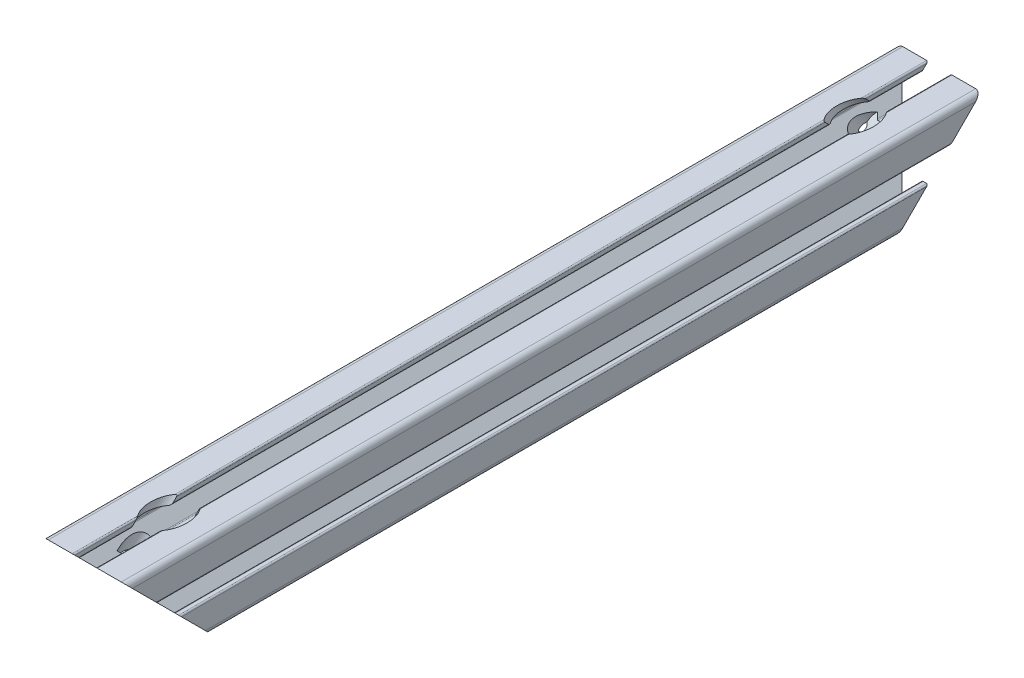
SolidWorks part; units mm, degrees
ref_plane "Front Plane" through (0, 0, 0) normal (0, 0, 1) x (1, 0, 0)
ref_plane "Top Plane" through (0, 0, 0) normal (0, 1, 0) x (1, 0, 0)
ref_plane "Right Plane" through (0, 0, 0) normal (1, 0, 0) x (0, 0, -1)
sketch "Sketch1" plane through (0, 0, 0) normal (0, 0, 1) x (1, 0, 0)
  line L0 (3.9799, -2.4733) -> (3.1981, -1.4942) construction
  line L1 (1.4942, -3.1981) -> (2.4733, -3.9799) construction
  line L2 (-2.4733, -3.9799) -> (-1.4942, -3.1981) construction
  line L3 (-3.1981, -1.4942) -> (-3.9799, -2.4733) construction
  line L4 (-3.9799, 2.4733) -> (-3.1981, 1.4942) construction
  line L5 (-1.4942, 3.1981) -> (-2.4733, 3.9799) construction
  line L6 (2.4733, 3.9799) -> (1.4942, 3.1981) construction
  line L7 (3.1981, 1.4942) -> (3.9799, 2.4733) construction
  line L8 (-12.6999, -13.6999) -> (-9.881, -13.6999)
  line L9 (-13.6999, -9.881) -> (-13.6999, -12.6999)
  line L10 (-9.88, -9.5) -> (-13.3189, -9.5)
  line L11 (-9.5, -13.3189) -> (-9.5, -9.88)
  line L12 (13.6999, -12.6999) -> (13.6999, -9.881)
  line L13 (9.881, -13.6999) -> (12.6999, -13.6999)
  line L14 (9.5, -9.88) -> (9.5, -13.3189)
  line L15 (13.3189, -9.5) -> (9.88, -9.5)
  line L16 (9.88, 9.5) -> (13.3189, 9.5)
  line L17 (9.5, 13.3189) -> (9.5, 9.88)
  line L18 (12.6999, 13.6999) -> (9.881, 13.6999)
  line L19 (13.6999, 9.881) -> (13.6999, 12.6999)
  line L20 (-13.6999, 12.6999) -> (-13.6999, 9.881)
  line L21 (-9.881, 13.6999) -> (-12.6999, 13.6999)
  line L22 (-9.5, 9.88) -> (-9.5, 13.3189)
  line L23 (-13.3189, 9.5) -> (-9.88, 9.5)
  line L24 (14.4999, -4) -> (13.2425, -4)
  line L25 (12.7425, -4.5) -> (12.7425, -7.7325)
  line L26 (12.2428, -8.25) -> (10.2602, -8.25)
  line L27 (9.9066, -8.1035) -> (5.9811, -4.178)
  line L28 (5.8347, -3.8245) -> (5.8347, -1.0125)
  line L29 (5.8347, -1.0125) -> (5.3247, -0.0625) construction
  line L30 (5.3247, -0.0625) -> (5.8347, 0.8875) construction
  line L31 (5.8347, 0.8875) -> (5.8347, 3.8245)
  line L32 (5.9811, 4.178) -> (9.9066, 8.1035)
  line L33 (10.2602, 8.25) -> (12.2428, 8.25)
  line L34 (12.7425, 7.7325) -> (12.7425, 4.5)
  line L35 (13.2425, 4) -> (14.4999, 4)
  line L36 (14.9999, 4.5) -> (14.9999, 12.9999)
  line L37 (12.9999, 14.9999) -> (4.5, 14.9999)
  line L38 (4, 14.4999) -> (4, 13.2425)
  line L39 (4.5, 12.7425) -> (7.7325, 12.7425)
  line L40 (8.25, 12.2428) -> (8.25, 10.2602)
  line L41 (8.1035, 9.9066) -> (4.178, 5.9811)
  line L42 (3.8245, 5.8347) -> (0.95, 5.8347)
  line L43 (0.95, 5.8347) -> (0, 5.3247) construction
  line L44 (0, 5.3247) -> (-0.95, 5.8347) construction
  line L45 (-0.95, 5.8347) -> (-3.8245, 5.8347)
  line L46 (-4.178, 5.9811) -> (-8.1035, 9.9066)
  line L47 (-8.25, 10.2602) -> (-8.25, 12.2428)
  line L48 (-7.7325, 12.7425) -> (-4.5, 12.7425)
  line L49 (-4, 13.2425) -> (-4, 14.4999)
  line L50 (-4.5, 14.9999) -> (-12.9999, 14.9999)
  line L51 (-14.9999, 12.9999) -> (-14.9999, 4.5)
  line L52 (-14.4999, 4) -> (-13.2425, 4)
  line L53 (-12.7425, 4.5) -> (-12.7425, 7.7325)
  line L54 (-12.2428, 8.25) -> (-10.2602, 8.25)
  line L55 (-9.9066, 8.1035) -> (-5.9811, 4.178)
  line L56 (-5.8347, 3.8245) -> (-5.8347, 0.8875)
  line L57 (-5.8347, 0.8875) -> (-5.3247, -0.0625) construction
  line L58 (-5.3247, -0.0625) -> (-5.8347, -1.0125) construction
  line L59 (-5.8347, -1.0125) -> (-5.8347, -3.8245)
  line L60 (-5.9811, -4.178) -> (-9.9066, -8.1035)
  line L61 (-10.2602, -8.25) -> (-12.2428, -8.25)
  line L62 (-12.7425, -7.7325) -> (-12.7425, -4.5)
  line L63 (-13.2425, -4) -> (-14.4999, -4)
  line L64 (-14.9999, -4.5) -> (-14.9999, -12.9999)
  line L65 (-12.9999, -14.9999) -> (-4.5, -14.9999)
  line L66 (-4, -14.4999) -> (-4, -13.2425)
  line L67 (-4.5, -12.7425) -> (-7.7325, -12.7425)
  line L68 (-8.25, -12.2428) -> (-8.25, -10.2602)
  line L69 (-8.1035, -9.9066) -> (-4.178, -5.9811)
  line L70 (-3.8245, -5.8347) -> (-0.95, -5.8347)
  line L71 (-0.95, -5.8347) -> (0, -5.3247) construction
  line L72 (0, -5.3247) -> (0.95, -5.8347) construction
  line L73 (0.95, -5.8347) -> (3.8245, -5.8347)
  line L74 (4.178, -5.9811) -> (8.1035, -9.9066)
  line L75 (8.25, -10.2602) -> (8.25, -12.2428)
  line L76 (7.7325, -12.7425) -> (4.5, -12.7425)
  line L77 (4, -13.2425) -> (4, -14.4999)
  line L78 (4.5, -14.9999) -> (12.9999, -14.9999)
  line L79 (14.9999, -12.9999) -> (14.9999, -4.5)
  line L80 (-5.8347, -1.0125) -> (-5.8347, 0.8875)
  line L81 (-0.95, 5.8347) -> (0.95, 5.8347)
  line L82 (5.8347, 0.8875) -> (5.8347, -1.0125)
  line L83 (-0.95, -5.8347) -> (0.95, -5.8347)
  arc A0 (2.4733, -3.9799) -> (3.9799, -2.4733) centre (3.1422, -3.1422) ccw construction
  arc A1 (-1.4942, -3.1981) -> (1.4942, -3.1981) centre (0, 0) ccw construction
  arc A2 (-3.9799, -2.4733) -> (-2.4733, -3.9799) centre (-3.1422, -3.1422) ccw construction
  arc A3 (-3.1981, 1.4942) -> (-3.1981, -1.4942) centre (0, 0) ccw construction
  arc A4 (-2.4733, 3.9799) -> (-3.9799, 2.4733) centre (-3.1422, 3.1422) ccw construction
  arc A5 (1.4942, 3.1981) -> (-1.4942, 3.1981) centre (0, 0) ccw construction
  arc A6 (3.9799, 2.4733) -> (2.4733, 3.9799) centre (3.1422, 3.1422) ccw construction
  arc A7 (3.1981, -1.4942) -> (3.1981, 1.4942) centre (0, 0) ccw construction
  arc A8 (-13.6999, -12.6999) -> (-12.6999, -13.6999) centre (-12.6999, -12.6999) ccw
  arc A9 (-13.3189, -9.5) -> (-13.6999, -9.881) centre (-13.3189, -9.881) ccw
  arc A10 (-9.5, -9.88) -> (-9.88, -9.5) centre (-9.88, -9.88) ccw
  arc A11 (-9.881, -13.6999) -> (-9.5, -13.3189) centre (-9.881, -13.3189) ccw
  arc A12 (12.6999, -13.6999) -> (13.6999, -12.6999) centre (12.6999, -12.6999) ccw
  arc A13 (9.5, -13.3189) -> (9.881, -13.6999) centre (9.881, -13.3189) ccw
  arc A14 (9.88, -9.5) -> (9.5, -9.88) centre (9.88, -9.88) ccw
  arc A15 (13.6999, -9.881) -> (13.3189, -9.5) centre (13.3189, -9.881) ccw
  arc A16 (9.5, 9.88) -> (9.88, 9.5) centre (9.88, 9.88) ccw
  arc A17 (9.881, 13.6999) -> (9.5, 13.3189) centre (9.881, 13.3189) ccw
  arc A18 (13.6999, 12.6999) -> (12.6999, 13.6999) centre (12.6999, 12.6999) ccw
  arc A19 (13.3189, 9.5) -> (13.6999, 9.881) centre (13.3189, 9.881) ccw
  arc A20 (14.9999, -4.5) -> (14.4999, -4) centre (14.4999, -4.5) ccw
  arc A21 (13.2425, -4) -> (12.7425, -4.5) centre (13.2425, -4.5) ccw
  arc A22 (12.2428, -8.25) -> (12.7425, -7.7325) centre (12.2428, -7.75) ccw
  arc A23 (9.9066, -8.1035) -> (10.2602, -8.25) centre (10.2602, -7.75) ccw
  arc A24 (5.8347, -3.8245) -> (5.9811, -4.178) centre (6.3347, -3.8245) ccw
  arc A25 (5.9811, 4.178) -> (5.8347, 3.8245) centre (6.3347, 3.8245) ccw
  arc A26 (10.2602, 8.25) -> (9.9066, 8.1035) centre (10.2602, 7.75) ccw
  arc A27 (12.7425, 7.7325) -> (12.2428, 8.25) centre (12.2428, 7.75) ccw
  arc A28 (12.7425, 4.5) -> (13.2425, 4) centre (13.2425, 4.5) ccw
  arc A29 (14.4999, 4) -> (14.9999, 4.5) centre (14.4999, 4.5) ccw
  arc A30 (14.9999, 12.9999) -> (12.9999, 14.9999) centre (12.9999, 12.9999) ccw
  arc A31 (4.5, 14.9999) -> (4, 14.4999) centre (4.5, 14.4999) ccw
  arc A32 (4, 13.2425) -> (4.5, 12.7425) centre (4.5, 13.2425) ccw
  arc A33 (8.25, 12.2428) -> (7.7325, 12.7425) centre (7.75, 12.2428) ccw
  arc A34 (8.1035, 9.9066) -> (8.25, 10.2602) centre (7.75, 10.2602) ccw
  arc A35 (3.8245, 5.8347) -> (4.178, 5.9811) centre (3.8245, 6.3347) ccw
  arc A36 (-4.178, 5.9811) -> (-3.8245, 5.8347) centre (-3.8245, 6.3347) ccw
  arc A37 (-8.25, 10.2602) -> (-8.1035, 9.9066) centre (-7.75, 10.2602) ccw
  arc A38 (-7.7325, 12.7425) -> (-8.25, 12.2428) centre (-7.75, 12.2428) ccw
  arc A39 (-4.5, 12.7425) -> (-4, 13.2425) centre (-4.5, 13.2425) ccw
  arc A40 (-4, 14.4999) -> (-4.5, 14.9999) centre (-4.5, 14.4999) ccw
  arc A41 (-12.9999, 14.9999) -> (-14.9999, 12.9999) centre (-12.9999, 12.9999) ccw
  arc A42 (-14.9999, 4.5) -> (-14.4999, 4) centre (-14.4999, 4.5) ccw
  arc A43 (-13.2425, 4) -> (-12.7425, 4.5) centre (-13.2425, 4.5) ccw
  arc A44 (-12.2428, 8.25) -> (-12.7425, 7.7325) centre (-12.2428, 7.75) ccw
  arc A45 (-9.9066, 8.1035) -> (-10.2602, 8.25) centre (-10.2602, 7.75) ccw
  arc A46 (-5.8347, 3.8245) -> (-5.9811, 4.178) centre (-6.3347, 3.8245) ccw
  arc A47 (-5.9811, -4.178) -> (-5.8347, -3.8245) centre (-6.3347, -3.8245) ccw
  arc A48 (-10.2602, -8.25) -> (-9.9066, -8.1035) centre (-10.2602, -7.75) ccw
  arc A49 (-12.7425, -7.7325) -> (-12.2428, -8.25) centre (-12.2428, -7.75) ccw
  arc A50 (-12.7425, -4.5) -> (-13.2425, -4) centre (-13.2425, -4.5) ccw
  arc A51 (-14.4999, -4) -> (-14.9999, -4.5) centre (-14.4999, -4.5) ccw
  arc A52 (-14.9999, -12.9999) -> (-12.9999, -14.9999) centre (-12.9999, -12.9999) ccw
  arc A53 (-4.5, -14.9999) -> (-4, -14.4999) centre (-4.5, -14.4999) ccw
  arc A54 (-4, -13.2425) -> (-4.5, -12.7425) centre (-4.5, -13.2425) ccw
  arc A55 (-8.25, -12.2428) -> (-7.7325, -12.7425) centre (-7.75, -12.2428) ccw
  arc A56 (-8.1035, -9.9066) -> (-8.25, -10.2602) centre (-7.75, -10.2602) ccw
  arc A57 (-3.8245, -5.8347) -> (-4.178, -5.9811) centre (-3.8245, -6.3347) ccw
  arc A58 (4.178, -5.9811) -> (3.8245, -5.8347) centre (3.8245, -6.3347) ccw
  arc A59 (8.25, -10.2602) -> (8.1035, -9.9066) centre (7.75, -10.2602) ccw
  arc A60 (7.7325, -12.7425) -> (8.25, -12.2428) centre (7.75, -12.2428) ccw
  arc A61 (4.5, -12.7425) -> (4, -13.2425) centre (4.5, -13.2425) ccw
  arc A62 (4, -14.4999) -> (4.5, -14.9999) centre (4.5, -14.4999) ccw
  arc A63 (12.9999, -14.9999) -> (14.9999, -12.9999) centre (12.9999, -12.9999) ccw
  arc A64 (-12.6999, 13.6999) -> (-13.6999, 12.6999) centre (-12.6999, 12.6999) ccw
  arc A65 (-9.5, 13.3189) -> (-9.881, 13.6999) centre (-9.881, 13.3189) ccw
  arc A66 (-9.88, 9.5) -> (-9.5, 9.88) centre (-9.88, 9.88) ccw
  arc A67 (-13.6999, 9.881) -> (-13.3189, 9.5) centre (-13.3189, 9.881) ccw
  circle A68 centre (0, 0) radius 3.53
extrude "Boss-Extrude1" add sketch "Sketch1" along normal mid plane 304.8
sketch "Sketch2" plane through (0, 0, 0) normal (1, 0, 0) x (0, 0, -1)
  line L0 (-152.4, 14.9999) -> (-152.4, -14.9999)
  line L1 (-152.4, -14.9999) -> (-122.4001, -14.9999)
  line L2 (-122.4001, -14.9999) -> (-152.4, 14.9999)
  line L3 (0, 0) -> (0, 14.9999) construction
  line L4 (-152.4, 14.9999) -> (152.4, 14.9999) construction
  line L5 (122.4001, -14.9999) -> (152.4, 14.9999)
  line L6 (152.4, -14.9999) -> (122.4001, -14.9999)
  line L7 (152.4, 14.9999) -> (152.4, -14.9999)
extrude "Cut-Extrude1" cut sketch "Sketch2" against normal through all and the other way through all
sketch "Sketch4" plane through (0, 0, 0) normal (1, 0, 0) x (0, 0, -1)
  line L0 (-152.4, -14.9999) -> (-117.8039, 19.5961) construction
  line L1 (-117.8039, 19.5961) -> (-122.4001, 24.1923)
  line L2 (-122.4001, 24.1923) -> (-137.5415, 9.051)
  line L3 (-137.5415, 9.051) -> (-135.1727, 6.6822)
  line L4 (-135.1727, 6.6822) -> (-139.6274, 2.2274)
  line L5 (-139.6274, 2.2274) -> (-137.4001, 0)
  line L6 (-113.2077, 14.9999) -> (-128.3491, -0.1414) construction
  line L7 (-152.4, 14.9999) -> (152.4, 14.9999) construction
  line L8 (-140.93, 3.53) -> (-133.8701, -3.53) construction
  line L9 (-122.4001, -14.9999) -> (-152.4, 14.9999) construction
  line L10 (-117.8039, 19.5961) -> (-137.4001, 0)
  dimension "D1" = 6.3
  dimension "D2" = 13
  dimension "D3" = 6.3
revolve "Cut-Revolve1" cut sketch "Sketch4" angle 360 mid plane about L0
mirror "Mirror1" about plane through (0, 0, 0) normal (0, 0, 1) of "Cut-Revolve1"
